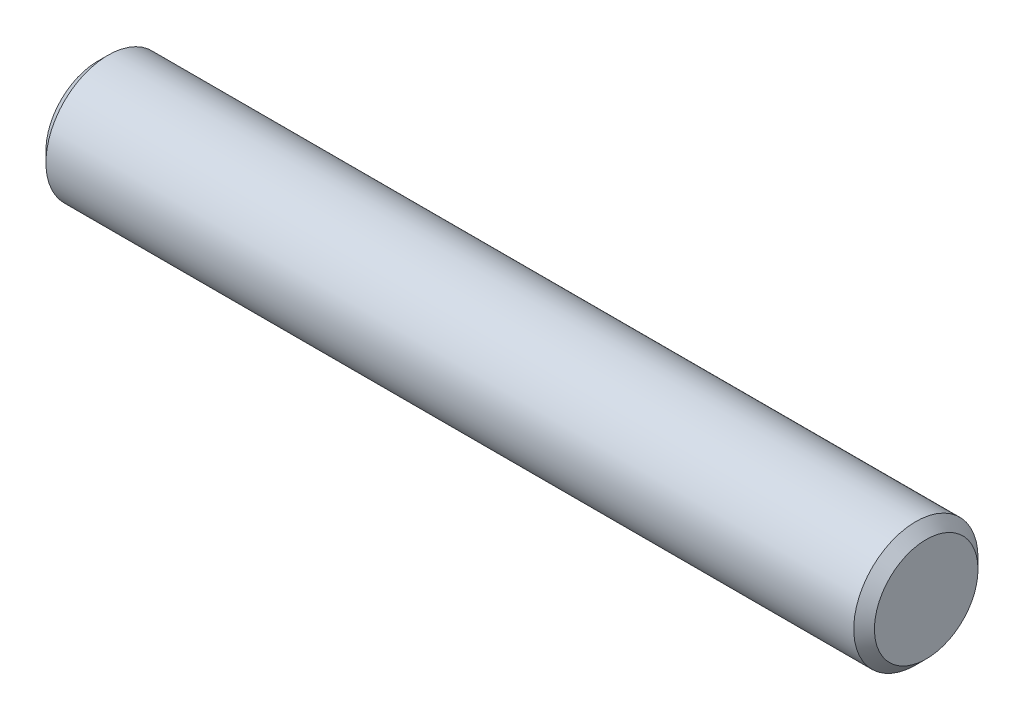
SolidWorks part; units mm, degrees
ref_plane "Front Plane" through (0, 0, 0) normal (0, 0, 1) x (1, 0, 0)
ref_plane "Top Plane" through (0, 0, 0) normal (0, 1, 0) x (1, 0, 0)
ref_plane "Right Plane" through (0, 0, 0) normal (1, 0, 0) x (0, 0, -1)
sketch "Sketch1" plane through (0, 0, 0) normal (1, 0, 0) x (0, 0, -1)
  circle A0 centre (0, 0) radius 1.5
  dimension "D1" = 3
extrude "Boss-Extrude1" add sketch "Sketch1" along normal mid plane 20
chamfer "Chamfer1" distance 0.25 angle 45 2 edges at (-10, 0, -1.5) (10, 0, -1.5)
